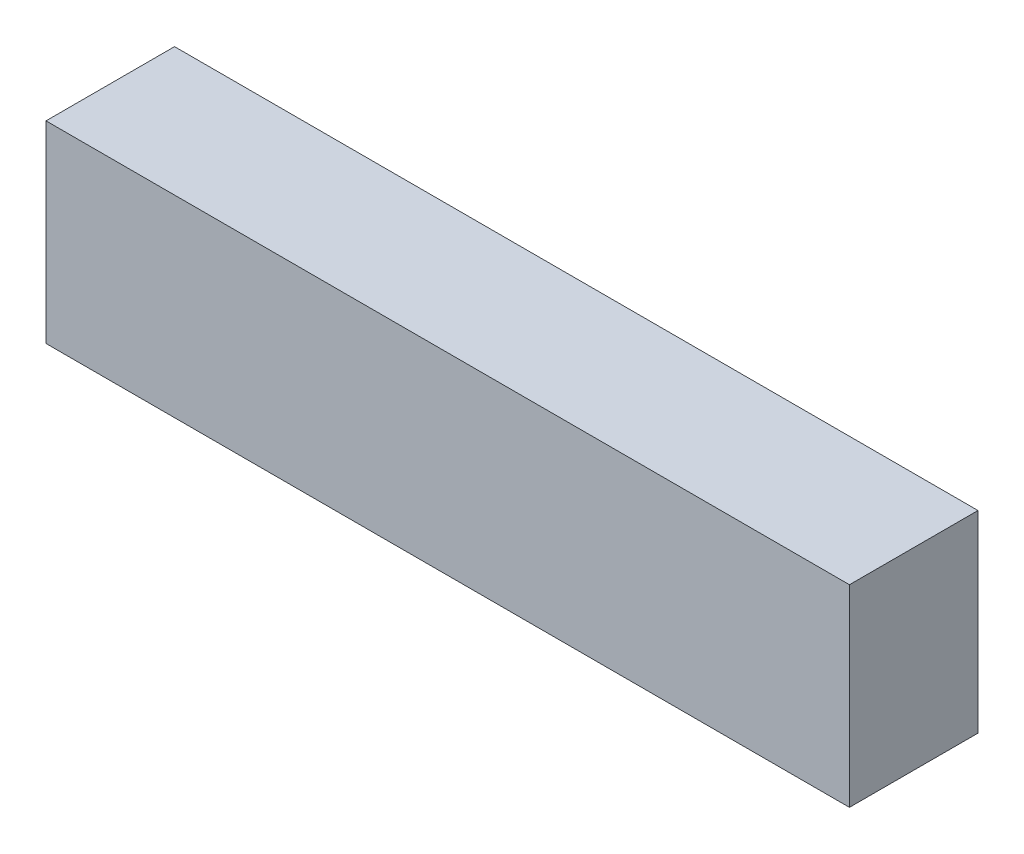
SolidWorks part; units mm, degrees
ref_plane "前视基准面" through (0, 0, 0) normal (0, 0, 1) x (1, 0, 0)
ref_plane "上视基准面" through (0, 0, 0) normal (0, 1, 0) x (1, 0, 0)
ref_plane "右视基准面" through (0, 0, 0) normal (1, 0, 0) x (0, 0, -1)
other "Configuration Table"
sketch "草图1" plane through (0, 0, 0) normal (0, 0, 1) x (1, 0, 0)
  line L1 (-25, -6) -> (25, -6)
  line L2 (-25, -6) -> (-25, 6)
  line L3 (-25, 6) -> (25, 6)
  line L4 (25, -6) -> (25, 6)
  line L5 (-25, -6) -> (25, 6) construction
  line L6 (-25, 6) -> (25, -6) construction
  point P0 (0, 0)
extrude "凸台-拉伸1" add sketch "草图1" along normal blind 8
